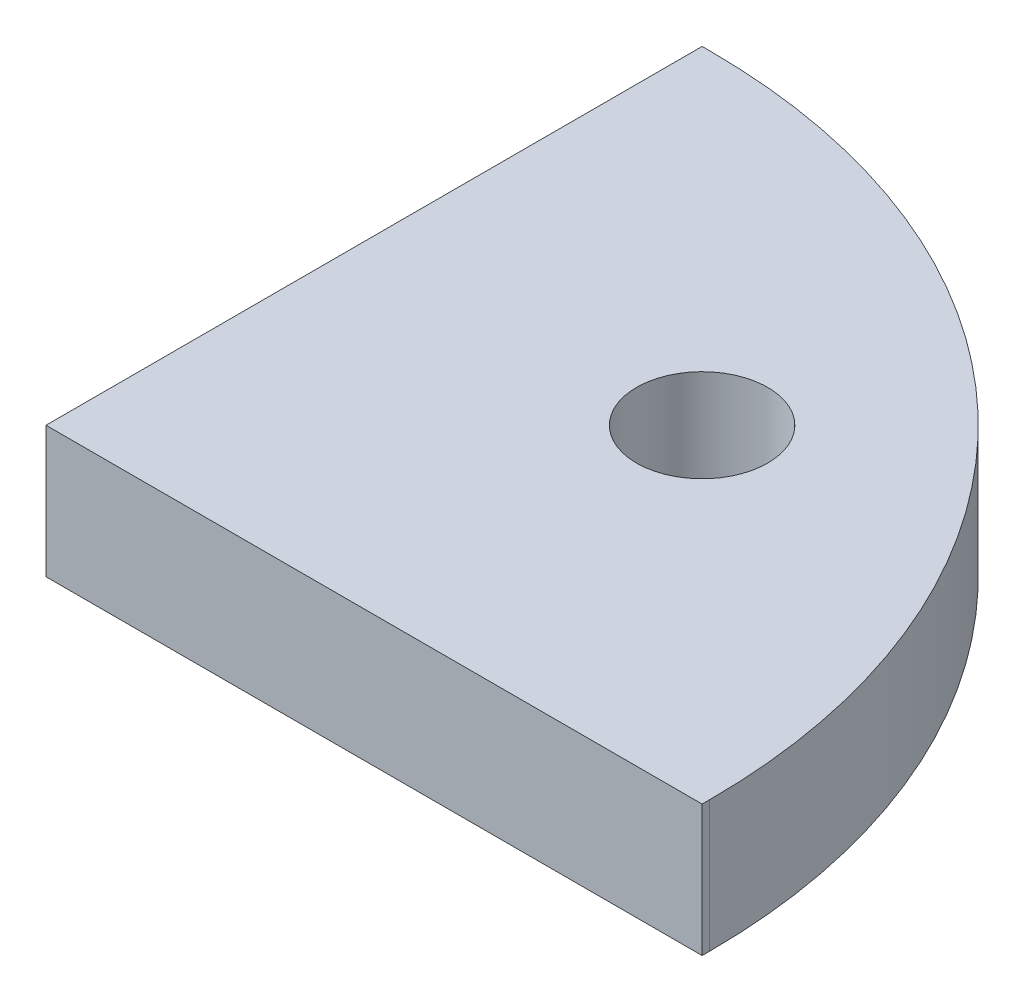
SolidWorks part; units mm, degrees
ref_plane "Alzado" through (0, 0, 0) normal (0, 0, 1) x (1, 0, 0)
ref_plane "Planta" through (0, 0, 0) normal (0, 1, 0) x (1, 0, 0)
ref_plane "Vista lateral" through (0, 0, 0) normal (1, 0, 0) x (0, 0, -1)
sketch "Croquis1" plane through (0, 0, 0) normal (0, 1, 0) x (1, 0, 0)
  line L1 (-25, -25) -> (25, -25)
  line L2 (-25, -25) -> (-25, 25)
  line L3 (-25, 25) -> (-24.4313, 25)
  line L4 (25, -25) -> (25, -24.4313)
  line L5 (-25, -25) -> (25, 25) construction
  line L6 (-25, 25) -> (25, -25) construction
  arc A0 (25, -24.4313) -> (-24.4313, 25) centre (-24.4313, -24.4313) ccw
  point P0 (0, 0)
  dimension "D3" = 49.4313
  dimension "D1" = 50
  dimension "D2" = 50
extrude "Saliente-Extruir1" add sketch "Croquis1" along normal blind 10
sketch "Croquis2" plane through (0, 10, 0) normal (0, 1, 0) x (1, 0, 0)
  circle A0 centre (0, 0) radius 5
extrude "Cortar-Extruir1" cut sketch "Croquis2" against normal blind 10
